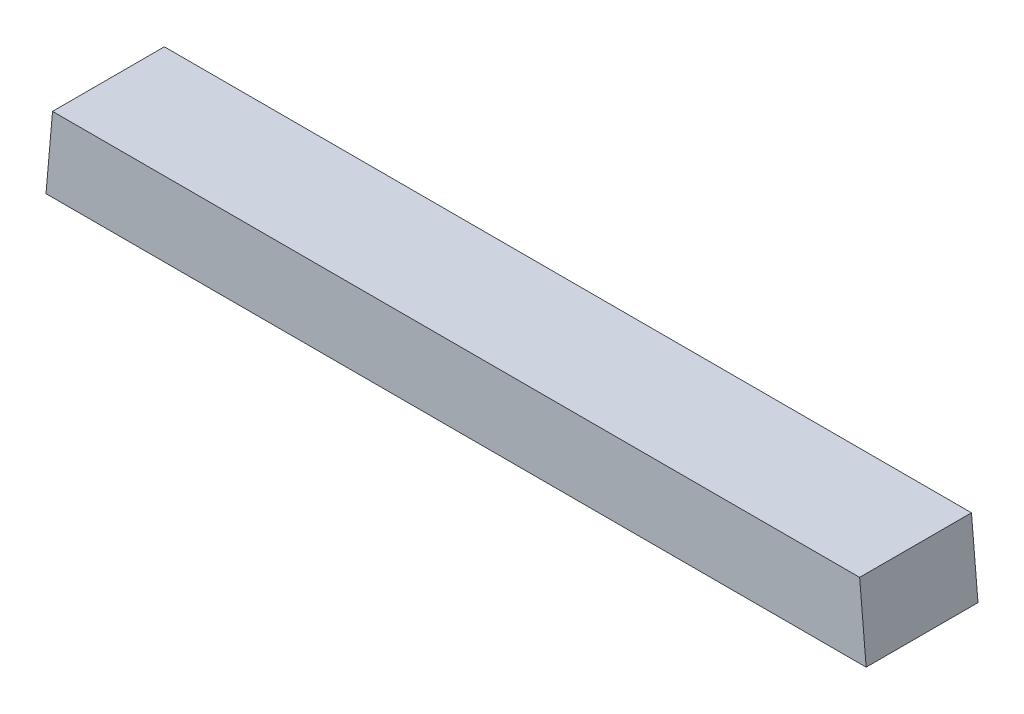
SolidWorks part; units mm, degrees
ref_plane "Plan de face" through (0, 0, 0) normal (0, 0, 1) x (1, 0, 0)
ref_plane "Plan de dessus" through (0, 0, 0) normal (0, 1, 0) x (1, 0, 0)
ref_plane "Plan de droite" through (0, 0, 0) normal (1, 0, 0) x (0, 0, -1)
sketch "Esquisse1" plane through (0, 0, 0) normal (0, 0, 1) x (1, 0, 0)
  line L1 (0, 0) -> (220, 0)
  line L2 (0, 0) -> (0, 20)
  line L3 (0, 20) -> (220, 20)
  line L4 (220, 0) -> (220, 20)
  dimension "D1" = 20
  dimension "D2" = 220
extrude "Boss.-Extru.1" add sketch "Esquisse1" along normal blind 30
sketch "Esquisse2" plane through (0, 0, 30) normal (0, 0, 1) x (1, 0, 0)
  line L0 (0, 0) -> (1.7498, 20)
  line L1 (220, 20) -> (0, 20) construction
  line L2 (1.7498, 20) -> (0, 20)
  line L3 (0, 20) -> (0, 0)
  line L4 (110, 0) -> (110, 20) construction
  line L5 (0, 0) -> (220, 0) construction
  line L6 (220, 20) -> (220, 0)
  line L7 (218.2502, 20) -> (220, 20)
  line L8 (220, 0) -> (218.2502, 20)
  dimension "D1" = 5
extrude "Enlèv. mat.-Extru.1" cut sketch "Esquisse2" against normal through all both and the other way through all
